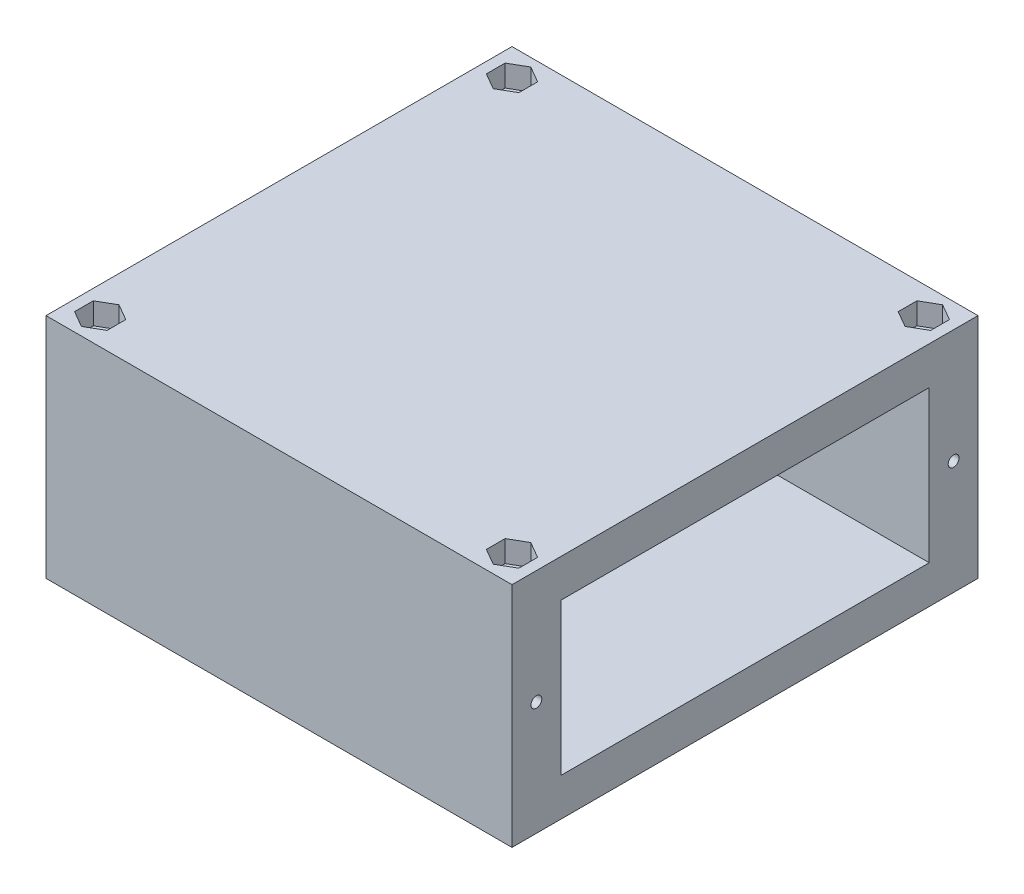
SolidWorks part; units mm, degrees
ref_plane "Plano frontal" through (0, 0, 0) normal (0, 0, 1) x (1, 0, 0)
ref_plane "Plano superior" through (0, 0, 0) normal (0, 1, 0) x (1, 0, 0)
ref_plane "Plano direito" through (0, 0, 0) normal (1, 0, 0) x (0, 0, -1)
sketch "Esboço1" plane through (0, 0, 0) normal (0, 1, 0) x (1, 0, 0)
  line L1 (-43, -43) -> (43, -43)
  line L2 (-43, -43) -> (-43, 43)
  line L3 (-43, 43) -> (43, 43)
  line L4 (43, -43) -> (43, 43)
  line L5 (-43, -43) -> (43, 43) construction
  line L6 (-43, 43) -> (43, -43) construction
  point P0 (0, 0)
  dimension "D1" = 86
extrude "Ressalto-extrusão1" add sketch "Esboço1" along normal mid plane 42
sketch "Esboço2" plane through (43, 0, 0) normal (1, 0, 0) x (0, 0, -1)
  line L1 (-34, -14) -> (34, -14)
  line L2 (-34, -14) -> (-34, 14)
  line L3 (-34, 14) -> (34, 14)
  line L4 (34, -14) -> (34, 14)
  line L5 (-34, -14) -> (34, 14) construction
  line L6 (-34, 14) -> (34, -14) construction
  point P0 (0, 0)
  dimension "D1" = 68
  dimension "D2" = 28
extrude "Corte-extrusão1" cut sketch "Esboço2" against normal blind 78
sketch "Esboço6" plane through (0, 21, 0) normal (0, 1, 0) x (1, 0, 0)
  line L1 (38, -38) -> (-38, -38) construction
  line L2 (38, -38) -> (38, 38) construction
  line L3 (38, 38) -> (-38, 38) construction
  line L4 (-38, -38) -> (-38, 38) construction
  line L5 (38, -38) -> (-38, 38) construction
  line L6 (38, 38) -> (-38, -38) construction
  circle A0 centre (-38, -38) radius 1.65
  circle A1 centre (-38, 38) radius 1.65
  circle A2 centre (38, 38) radius 1.65
  circle A3 centre (38, -38) radius 1.65
  point P0 (0, 0)
  dimension "D2" = 3.3
  dimension "D1" = 76
extrude "Corte-extrusão3" cut sketch "Esboço6" against normal blind 9
sketch "Esboço7" plane through (0, 21, 0) normal (0, 1, 0) x (1, 0, 0)
  line L1 (-38, -34.5359) -> (-41, -36.2679)
  line L2 (-41, -36.2679) -> (-41, -39.7321)
  line L3 (-41, -39.7321) -> (-38, -41.4641)
  line L4 (-38, -41.4641) -> (-35, -39.7321)
  line L5 (-35, -39.7321) -> (-35, -36.2679)
  line L6 (-35, -36.2679) -> (-38, -34.5359)
  circle A0 centre (-38, -38) radius 3 construction
  dimension "D1" = 6
extrude "Corte-extrusão4" cut sketch "Esboço7" against normal blind 4
mirror "Espelhar1" about plane through (0, 0, 0) normal (0, 0, 1) of "Corte-extrusão4"
mirror "Espelhar2" about plane through (0, 0, 0) normal (1, 0, 0) of "Corte-extrusão4", "Espelhar1"
sketch "Esboço8" plane through (0, -21, 0) normal (0, -1, 0) x (1, 0, 0)
  line L1 (-38, 38) -> (38, 38) construction
  line L2 (-38, 38) -> (-38, -38) construction
  line L3 (-38, -38) -> (38, -38) construction
  line L4 (38, 38) -> (38, -38) construction
  line L5 (-38, 38) -> (38, -38) construction
  line L6 (-38, -38) -> (38, 38) construction
  circle A0 centre (38, 38) radius 1.65
  circle A1 centre (38, -38) radius 1.65
  circle A2 centre (-38, -38) radius 1.65
  circle A3 centre (-38, 38) radius 1.65
  point P0 (0, 0)
  dimension "D2" = 3.3
  dimension "D1" = 76
extrude "Corte-extrusão5" cut sketch "Esboço8" against normal blind 9
mirror "Espelhar4" about plane through (0, 0, 0) normal (0, 1, 0) of "Espelhar2", "Espelhar1", "Corte-extrusão4"
sketch "Esboço9" plane through (43, 0, 0) normal (1, 0, 0) x (0, 0, -1)
  line L0 (-43, 0) -> (-34, 0) construction
  line L1 (-43, 21) -> (-43, -21) construction
  line L2 (-34, 14) -> (-34, -14) construction
  line L3 (34, 0) -> (43, 0) construction
  line L4 (34, -14) -> (34, 14) construction
  line L5 (43, 21) -> (43, -21) construction
  circle A0 centre (-38.5, 0) radius 1
  circle A1 centre (38.5, 0) radius 1
  dimension "D1" = 2
  dimension "D2" = 4.5
extrude "Corte-extrusão6" cut sketch "Esboço9" against normal blind 6
